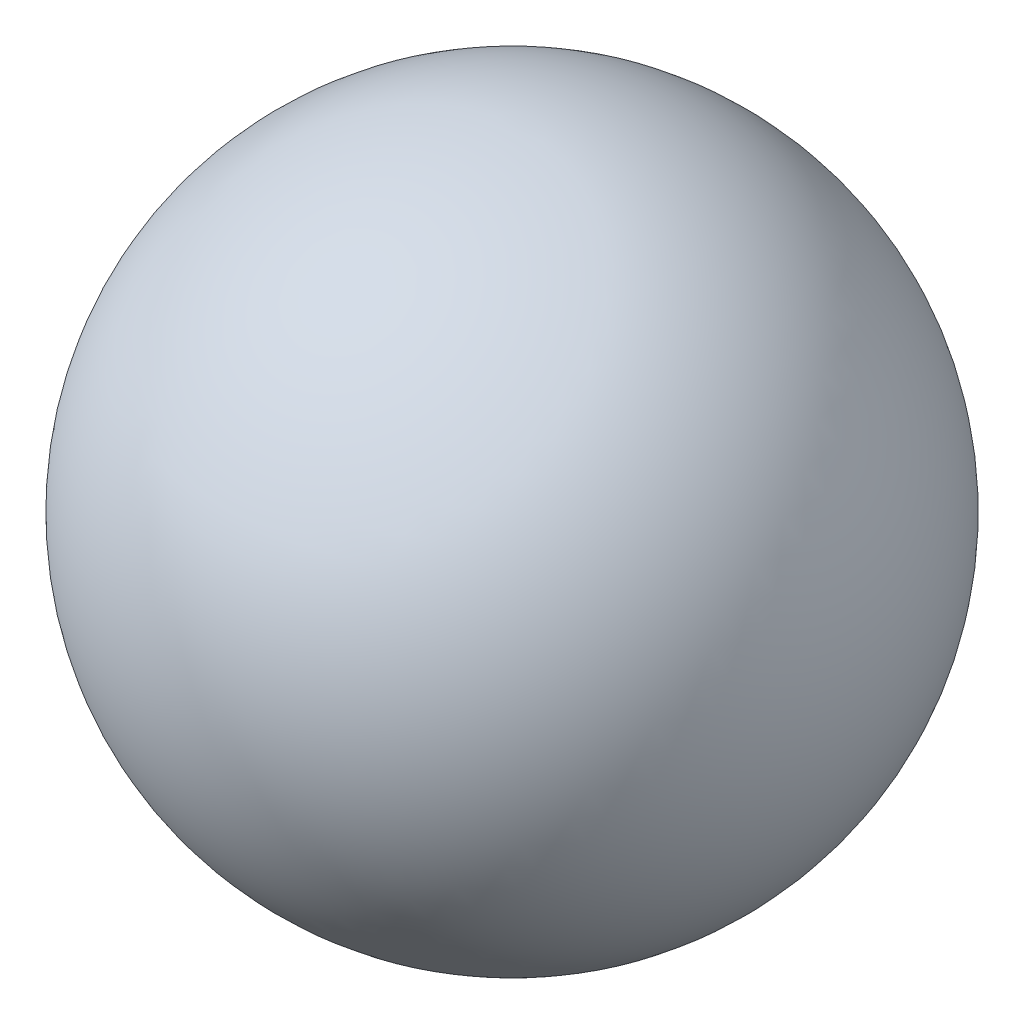
SolidWorks part; units mm, degrees
ref_plane "Ön Düzlem" through (0, 0, 0) normal (0, 0, 1) x (1, 0, 0)
ref_plane "Üst Düzlem" through (0, 0, 0) normal (0, 1, 0) x (1, 0, 0)
ref_plane "Sağ Düzlem" through (0, 0, 0) normal (1, 0, 0) x (0, 0, -1)
sketch "Sketch1" plane through (0, 0, 0) normal (0, 0, 1) x (1, 0, 0)
  line L0 (0, 32.5) -> (0, -32.5)
  arc A0 (0, -32.5) -> (0, 32.5) centre (0, 0) ccw
revolve "Revolve2" add sketch "Sketch1" angle 360 about L0
